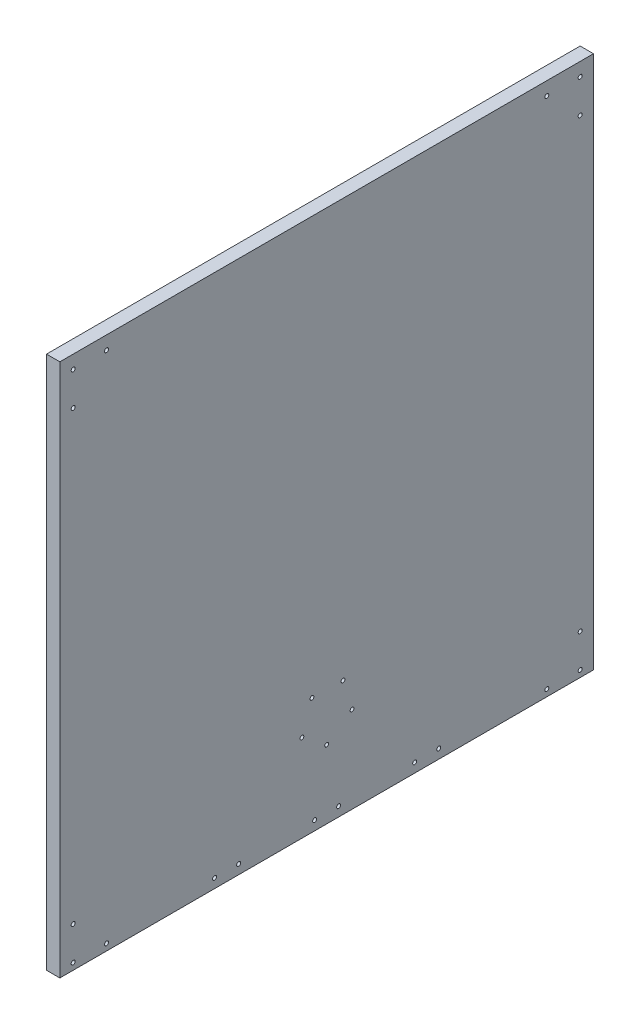
SolidWorks part; units mm, degrees
ref_plane "前视基准面" through (0, 0, 0) normal (0, 0, 1) x (1, 0, 0)
ref_plane "上视基准面" through (0, 0, 0) normal (0, 1, 0) x (1, 0, 0)
ref_plane "右视基准面" through (0, 0, 0) normal (1, 0, 0) x (0, 0, -1)
sketch "草图1" plane through (0, 0, 0) normal (1, 0, 0) x (0, 0, -1)
  line L1 (-200, 200) -> (200, 200)
  line L2 (-200, 200) -> (-200, -200)
  line L3 (-200, -200) -> (200, -200)
  line L4 (200, 200) -> (200, -200)
  line L5 (-200, 200) -> (200, -200) construction
  line L6 (-200, -200) -> (200, 200) construction
  point P0 (0, 0)
  dimension "D1" = 400
  dimension "D2" = 400
extrude "凸台-拉伸1" add sketch "草图1" along normal blind 10
sketch "草图2" plane through (10, 0, 0) normal (1, 0, 0) x (0, 0, -1)
  line L0 (200, 200) -> (200, -200) construction
  line L3 (165, 190) -> (190, 190) construction
  line L4 (190, 165) -> (190, 190) construction
  line L5 (165, -195) -> (190, -195) construction
  line L6 (165, 190) -> (190, 165) construction
  line L7 (-200, 200) -> (200, 200) construction
  line L8 (190, -195) -> (190, -170) construction
  line L9 (-200, -200) -> (200, -200) construction
  circle A0 centre (190, 190) radius 1.5
  circle A1 centre (165, 190) radius 1.5
  circle A2 centre (190, 165) radius 1.5
  circle A3 centre (190, -195) radius 1.5
  circle A4 centre (165, -195) radius 1.5
  circle A5 centre (190, -170) radius 1.5
  point P0 (176.0995, 178.9005)
  dimension "D5" = 3
  dimension "D6" = 3
  dimension "D7" = 3
  dimension "D1" = 25
  dimension "D2" = 25
  dimension "D3" = 10
  dimension "D4" = 10
  dimension "D8" = 25
  dimension "D9" = 25
  dimension "D10" = 5
  dimension "D11" = 10
extrude "切除-拉伸1" cut sketch "草图2" against normal blind 10
sketch "草图3" plane through (10, 0, 0) normal (1, 0, 0) x (0, 0, -1)
  line L0 (-84, -193) -> (-66, -193) construction
  line L1 (-66, -193) -> (-9, -193) construction
  line L2 (-9, -193) -> (9, -193) construction
  line L3 (9, -193) -> (66, -193) construction
  line L4 (66, -193) -> (84, -193) construction
  line L5 (-200, -200) -> (200, -200) construction
  line L6 (-200, 200) -> (-200, -200) construction
  circle A0 centre (-84, -193) radius 1.5
  circle A1 centre (-66, -193) radius 1.5
  circle A2 centre (-9, -193) radius 1.5
  circle A3 centre (9, -193) radius 1.5
  circle A4 centre (66, -193) radius 1.5
  circle A5 centre (84, -193) radius 1.5
  dimension "D1" = 3
  dimension "D2" = 3
  dimension "D3" = 3
  dimension "D4" = 3
  dimension "D5" = 3
  dimension "D6" = 3
  dimension "D7" = 7
  dimension "D8" = 116
  dimension "D9" = 18
  dimension "D10" = 18
  dimension "D11" = 18
  dimension "D12" = 57
  dimension "D13" = 57
extrude "切除-拉伸2" cut sketch "草图3" against normal blind 10
mirror "镜向1" about plane through (0, 0, 0) normal (0, 0, 1) of "切除-拉伸1"
sketch "草图4" plane through (10, 0, 0) normal (1, 0, 0) x (0, 0, -1)
  line L0 (-200, -200) -> (200, -200) construction
  line L1 (19.0413, -135.2539) -> (12.238, -113.0222) construction
  line L2 (12.238, -113.0222) -> (-11.0079, -112.6225) construction
  line L3 (-11.0079, -112.6225) -> (-18.5714, -134.6072) construction
  line L4 (-18.5714, -134.6072) -> (0, -148.5942) construction
  line L5 (0, -148.5942) -> (19.0413, -135.2539) construction
  line L7 (200, 200) -> (200, -200) construction
  circle A0 centre (0.34, -128.82) radius 16 construction
  circle A1 centre (-11.0079, -112.6225) radius 1.45
  circle A2 centre (12.238, -113.0222) radius 1.45
  circle A3 centre (-18.5714, -134.6072) radius 1.45
  circle A4 centre (19.0413, -135.2539) radius 1.45
  circle A5 centre (0, -148.5942) radius 1.45
  dimension "D1" = 32
  dimension "D3" = 2.9
  dimension "D4" = 2.9
  dimension "D5" = 2.9
  dimension "D6" = 2.9
  dimension "D7" = 2.9
  dimension "D2" = 71.18
  dimension "D8" = 199.66
extrude "切除-拉伸3" cut sketch "草图4" against normal blind 10
